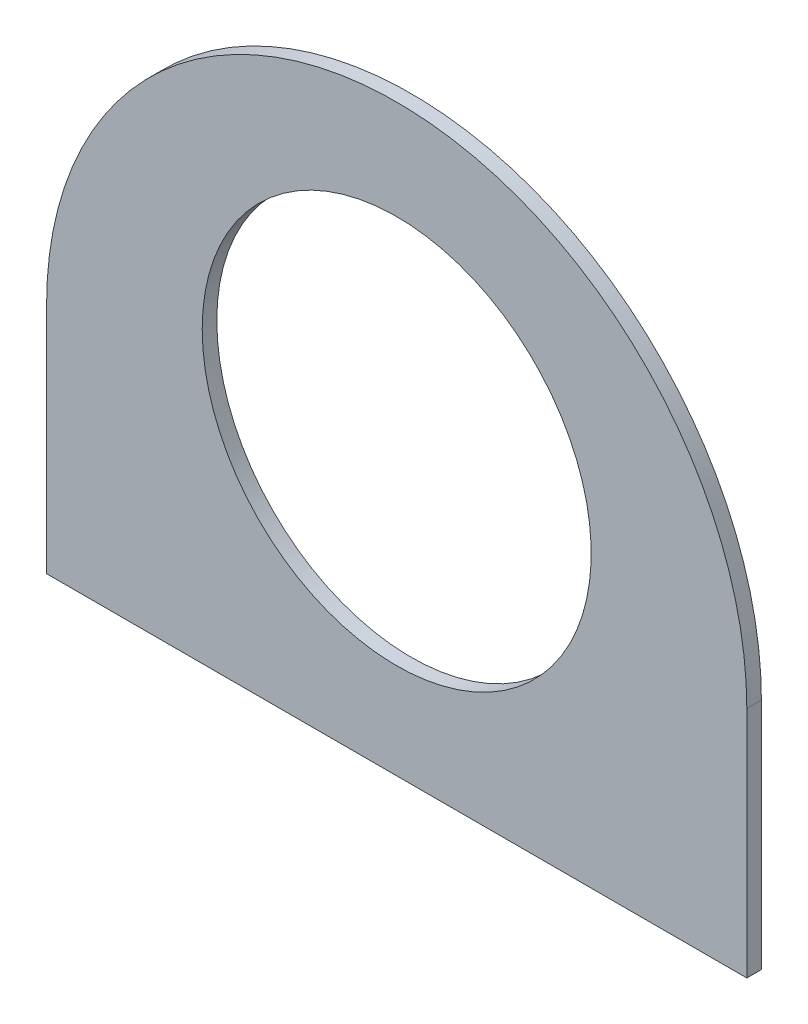
SolidWorks part; units mm, degrees
ref_plane "Front Plane" through (0, 0, 0) normal (0, 0, 1) x (1, 0, 0)
ref_plane "Top Plane" through (0, 0, 0) normal (0, 1, 0) x (1, 0, 0)
ref_plane "Right Plane" through (0, 0, 0) normal (1, 0, 0) x (0, 0, -1)
sketch "Sketch1" plane through (0, 0, 0) normal (0, 0, 1) x (1, 0, 0)
  line L0 (-228.6, -36.83) -> (-228.6, -189.23)
  line L1 (-228.6, -189.23) -> (228.6, -189.23)
  line L2 (-228.6, -189.23) -> (-228.6, 191.77) construction
  line L3 (-228.6, 191.77) -> (228.6, 191.77) construction
  line L4 (228.6, -189.23) -> (228.6, 191.77) construction
  line L5 (228.6, -36.83) -> (228.6, -189.23)
  circle A0 centre (0, 0) radius 127
  arc A2 (228.6, -36.83) -> (-228.6, -36.83) centre (0, -36.83) ccw
  dimension "D1" = 254
  dimension "D4" = 189.23
  dimension "D5" = 228.6
  dimension "D2" = 457.2
  dimension "D3" = 381
extrude "Boss-Extrude1" add sketch "Sketch1" along normal blind 9.525
